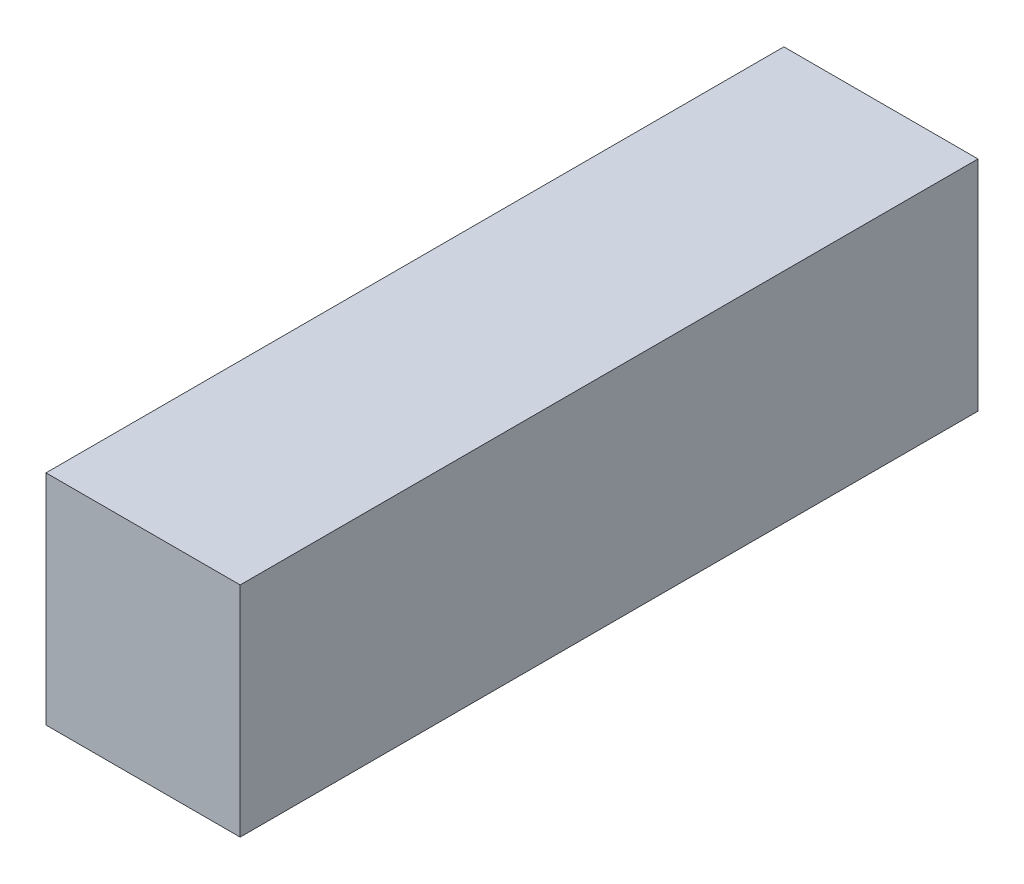
SolidWorks part; units mm, degrees
ref_plane "Front Plane" through (0, 0, 0) normal (0, 0, 1) x (1, 0, 0)
ref_plane "Top Plane" through (0, 0, 0) normal (0, 1, 0) x (1, 0, 0)
ref_plane "Right Plane" through (0, 0, 0) normal (1, 0, 0) x (0, 0, -1)
sketch "Sketch1" plane through (0, 0, 0) normal (1, 0, 0) x (0, 0, -1)
  line L1 (0, 0) -> (48.26, 0)
  line L2 (0, 0) -> (0, 14.2875)
  line L3 (0, 14.2875) -> (48.26, 14.2875)
  line L4 (48.26, 0) -> (48.26, 14.2875)
  dimension "D1" = 48.26
  dimension "D2" = 14.2875
extrude "Boss-Extrude1" add sketch "Sketch1" along normal blind 12.7
